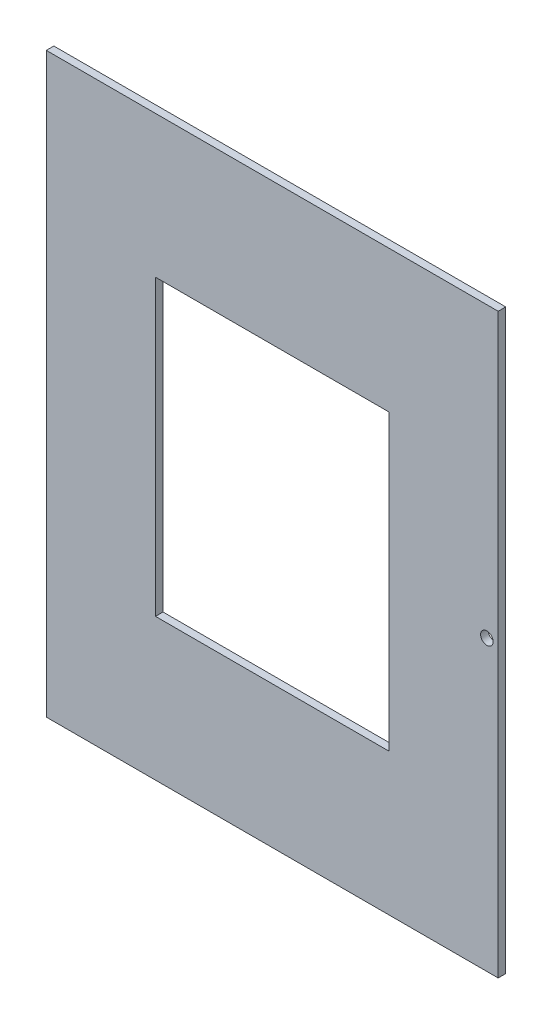
SolidWorks part; units mm, degrees
ref_plane "Alzado" through (0, 0, 0) normal (0, 0, 1) x (1, 0, 0)
ref_plane "Planta" through (0, 0, 0) normal (0, 1, 0) x (1, 0, 0)
ref_plane "Vista lateral" through (0, 0, 0) normal (1, 0, 0) x (0, 0, -1)
sketch "Croquis1" plane through (0, 0, 0) normal (0, 0, 1) x (1, 0, 0)
  line L0 (0, 0) -> (180, 0)
  line L1 (180, 0) -> (180, -230)
  line L2 (0, 0) -> (0, -230)
  line L3 (0, -230) -> (180, -230)
  line L4 (0, 0) -> (180, -230) construction
  line L5 (180, 0) -> (0, -230) construction
  line L6 (90, -115) -> (180, -115) construction
  line L7 (180, -115) -> (0, -115) construction
  line L8 (90, -56.5) -> (43.5, -56.5)
  line L9 (90, -56.5) -> (136.5, -56.5)
  line L10 (43.5, -56.5) -> (43.5, -173.5)
  line L11 (43.5, -173.5) -> (136.5, -173.5)
  line L12 (136.5, -56.5) -> (136.5, -173.5)
  line L13 (43.5, -56.5) -> (136.5, -173.5) construction
  line L14 (43.5, -173.5) -> (136.5, -56.5)
  line L15 (180, -115) -> (175.5, -115) construction
  circle A0 centre (175.5, -115) radius 2.5
  point P7 (90, -115)
  dimension "D8" = 5
  dimension "D1" = 180
  dimension "D2" = 230
  dimension "D3" = 180
  dimension "D4" = 230
  dimension "D5" = 4.5
  dimension "D6" = 46.5
  dimension "D7" = 117
extrude "Saliente-Extruir1" add sketch "Croquis1" along normal blind 3 contours L2 L3 L1 L0 A0 L9 L12 L11 L10 L8
